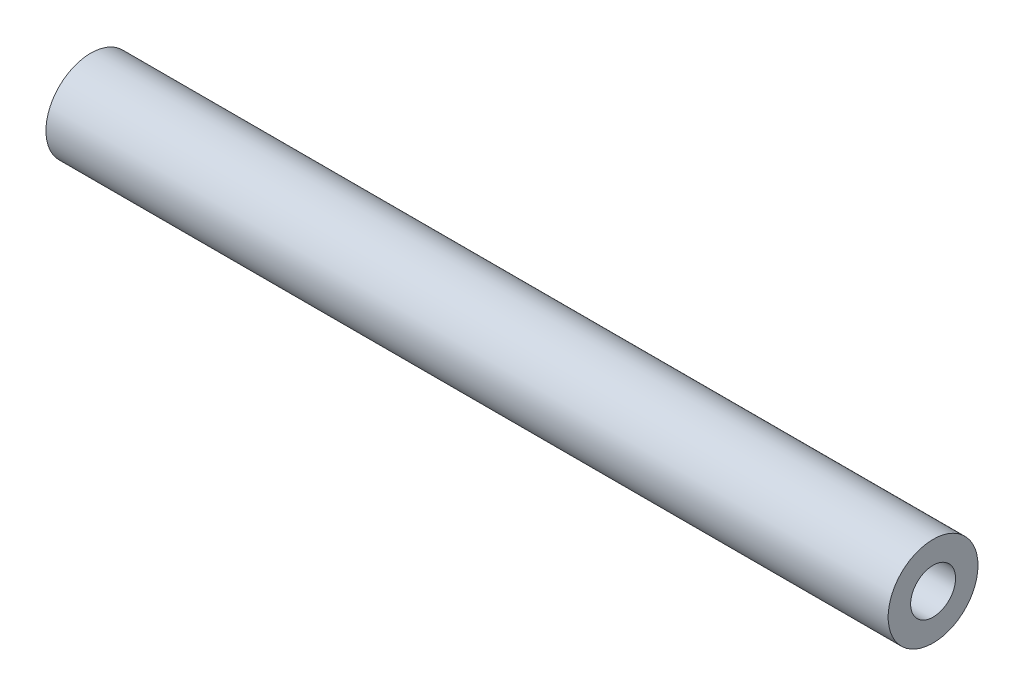
SolidWorks part; units mm, degrees
material "Oak"
ref_plane "Front" through (0, 0, 0) normal (0, 0, 1) x (1, 0, 0)
ref_plane "Top" through (0, 0, 0) normal (0, 1, 0) x (1, 0, 0)
ref_plane "Right" through (0, 0, 0) normal (1, 0, 0) x (0, 0, -1)
sketch "Sketch1" plane through (0, 0, 0) normal (1, 0, 0) x (0, 0, -1)
  circle A0 centre (0, 0) radius 4
  dimension "D1" = 8
extrude "Boss-Extrude1" add sketch "Sketch1" along normal mid plane 75
sketch "Sketch2" plane through (37.5, 0, 0) normal (1, 0, 0) x (0, 0, -1)
  circle A0 centre (0, 0) radius 2
  dimension "D1" = 4
extrude "Cut-Extrude1" cut sketch "Sketch2" against normal blind 15
mirror "Mirror1" about plane through (0, 0, 0) normal (1, 0, 0) of "Cut-Extrude1"
